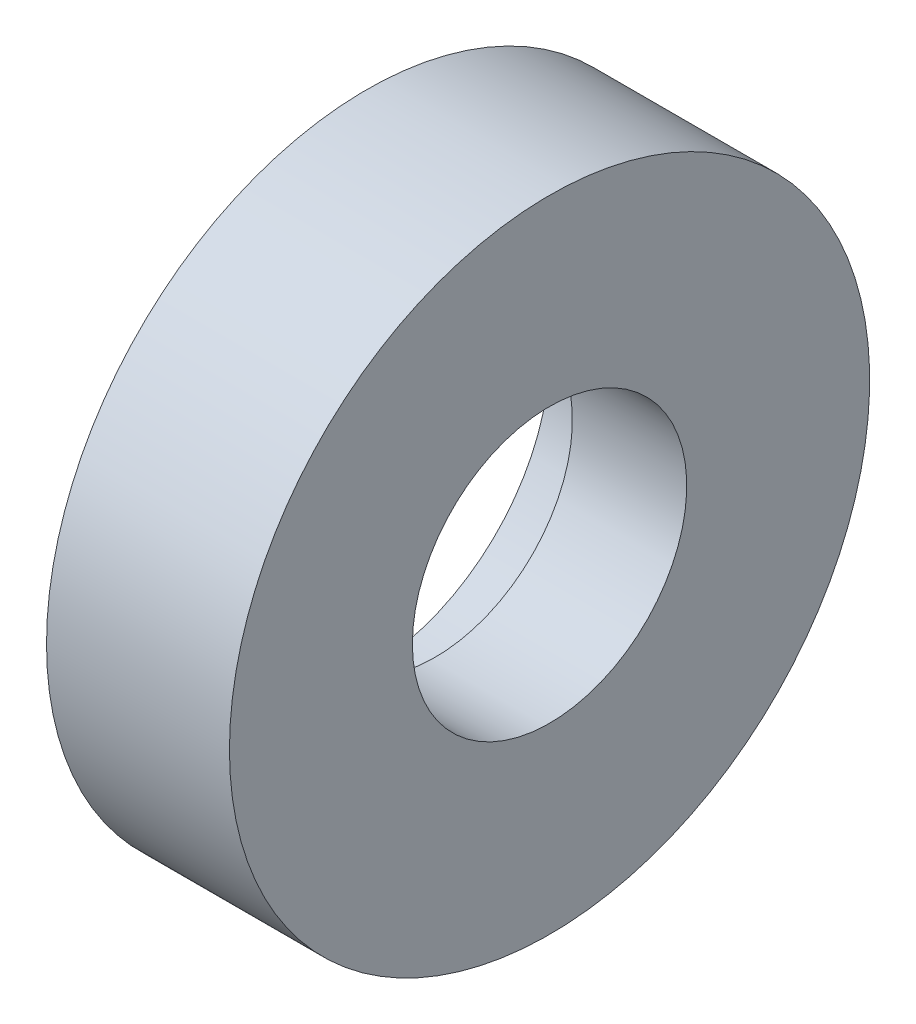
SolidWorks part; units mm, degrees
material "Rubber"
ref_plane "Front Plane" through (0, 0, 0) normal (0, 0, 1) x (1, 0, 0)
ref_plane "Top Plane" through (0, 0, 0) normal (0, 1, 0) x (1, 0, 0)
ref_plane "Right Plane" through (0, 0, 0) normal (1, 0, 0) x (0, 0, -1)
sketch "Sketch2" plane through (0, 0, 0) normal (0, 0, 1) x (1, 0, 0)
  line L0 (0, 0) -> (75.939, 0)
sketch "Sketch3" plane through (0, 0, 0) normal (0, 1, 0) x (1, 0, 0)
  line L0 (8.5886, 14) -> (8.5886, 8)
  line L1 (8.5886, 8) -> (11.5886, 8)
  line L2 (11.5886, 8) -> (11.5886, 6)
  line L3 (11.5886, 6) -> (16.5886, 6)
  line L4 (16.5886, 6) -> (16.5886, 14)
  line L5 (16.5886, 14) -> (8.5886, 14)
  line L6 (0, 0) -> (75.939, 0) construction
  dimension "D1" = 3
  dimension "D2" = 5
  dimension "D3" = 8
  dimension "D4" = 6
  dimension "D5" = 6
revolve "Revolve1" add sketch "Sketch3" angle 360 about L0
